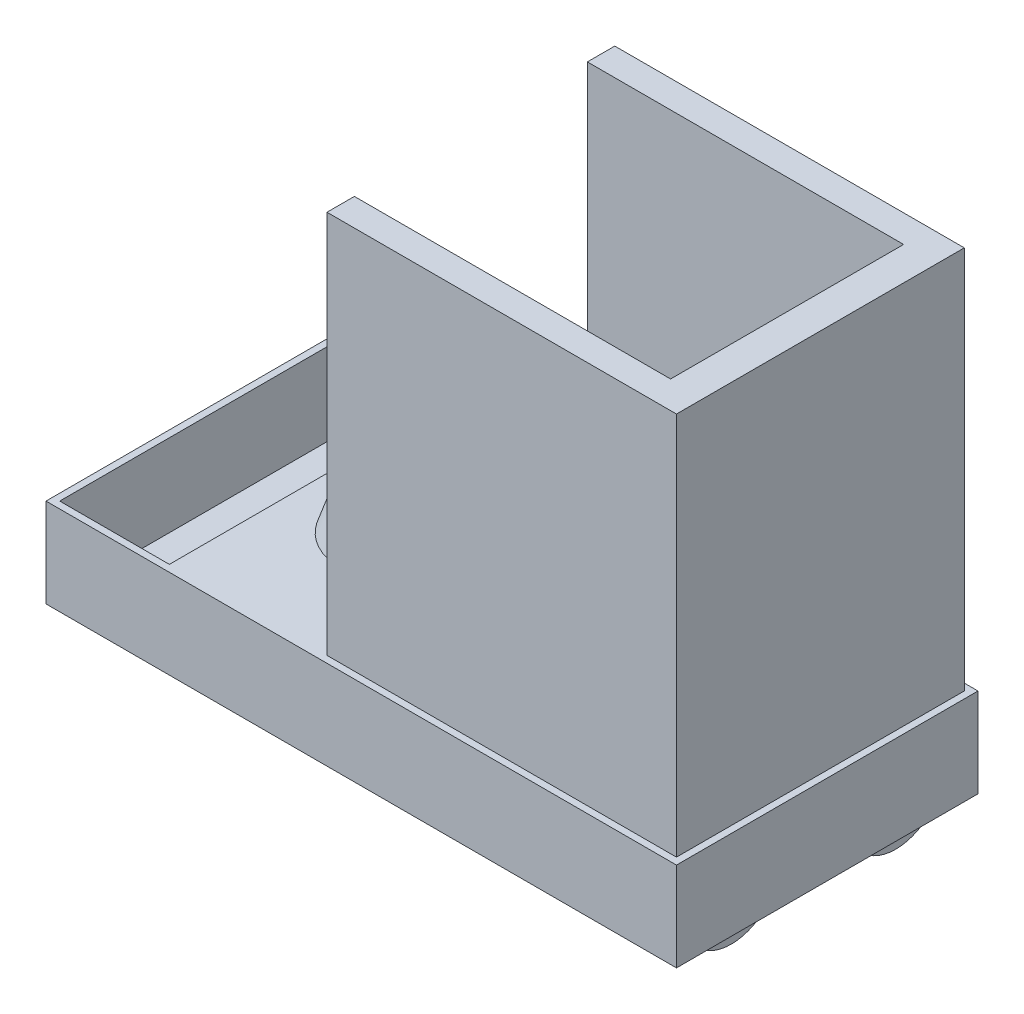
SolidWorks part; units mm, degrees
ref_plane "Front Plane" through (0, 0, 0) normal (0, 0, 1) x (1, 0, 0)
ref_plane "Top Plane" through (0, 0, 0) normal (0, 1, 0) x (1, 0, 0)
ref_plane "Right Plane" through (0, 0, 0) normal (1, 0, 0) x (0, 0, -1)
sketch "Chasis" plane through (0, 0, 0) normal (0, 1, 0) x (1, 0, 0)
  line L1 (-228.6, -139.7) -> (228.6, -139.7)
  line L2 (-228.6, -139.7) -> (-228.6, 139.7)
  line L3 (-228.6, 139.7) -> (228.6, 139.7)
  line L4 (228.6, -139.7) -> (228.6, 139.7)
  line L5 (-228.6, -139.7) -> (228.6, 139.7) construction
  line L6 (-228.6, 139.7) -> (228.6, -139.7) construction
  point P0 (0, 0)
  dimension "D1" = 457.2
  dimension "D2" = 279.4
extrude "Boss-Extrude1" add sketch "Chasis" along normal blind 82.55 contours L3 L4 L1 L2
ref_plane "Plane1" through (0, 25.4, 0) normal (0, -1, 0) x (-1, 0, 0)
sketch "Sketch3" plane through (0, 25.4, 0) normal (0, -1, 0) x (-1, 0, 0)
  line L0 (215.9, -76.2) -> (171.45, -76.2)
  line L1 (215.9, -76.2) -> (215.9, -120.65)
  line L2 (215.9, -120.65) -> (171.45, -120.65)
  line L3 (171.45, -76.2) -> (171.45, -120.65)
  line L4 (228.6, -139.7) -> (228.6, 139.7) construction
  line L5 (228.6, -139.7) -> (-228.6, -139.7) construction
  dimension "D1" = 44.45
  dimension "D2" = 44.45
  dimension "D3" = 12.7
  dimension "D4" = 19.05
revolve "Revolve1" add sketch "Sketch3" angle 360 about L0
mirror "Mirror1" about plane through (0, 0, 0) normal (0, 0, 1) of "Revolve1"
mirror "Mirror2" about plane through (0, 0, 0) normal (1, 0, 0) of "Revolve1", "Mirror1"
sketch "Sketch4" plane through (0, 82.55, 0) normal (0, 1, 0) x (1, 0, 0)
  line L0 (-228.6, -139.7) -> (228.6, -139.7) construction
  line L1 (222.25, 133.35) -> (-101.6, 133.35)
  line L2 (222.25, 133.35) -> (222.25, -133.35)
  line L3 (222.25, -133.35) -> (-101.6, -133.35)
  line L4 (-101.6, 133.35) -> (-101.6, 107.95)
  line L5 (222.25, 133.35) -> (-101.6, -133.35) construction
  line L6 (222.25, -133.35) -> (-101.6, 133.35) construction
  line L7 (228.6, -139.7) -> (228.6, 139.7) construction
  line L9 (-228.6, 139.7) -> (228.6, 139.7) construction
  line L10 (-101.6, 107.95) -> (191.4071, 107.95)
  line L11 (191.4071, 107.95) -> (191.4071, -107.95)
  line L12 (191.4071, -107.95) -> (-101.6, -107.95)
  line L13 (-101.6, -107.95) -> (-101.6, -133.35)
  point P0 (60.325, 0)
  point P5 (-128.4089, 107.95)
  point P13 (-156.7602, -108.6346)
  point P14 (244.9811, -107.95)
  dimension "D1" = 6.35
  dimension "D2" = 6.35
  dimension "D3" = 127
  dimension "D4" = 6.35
  dimension "D6" = 215.9
extrude "Boss-Extrude2" add sketch "Sketch4" along normal blind 355.6 contours L2 L3 L13 L12 L11 L10 L4 L1
sketch "Sketch5" plane through (0, 82.55, 0) normal (0, 1, 0) x (1, 0, 0)
  line L0 (-228.6, -139.7) -> (-228.6, 139.7) construction
  line L1 (-228.6, 139.7) -> (228.6, 139.7) construction
  circle A0 centre (-165.1, 0) radius 57.15
  point P4 (-165.1, 0)
  dimension "D1" = 114.3
  dimension "D3" = 139.7
  dimension "D2" = 63.5
ref_plane "Plane2" through (0, 120.65, 0) normal (0, 1, 0) x (1, 0, 0)
sketch "Sketch6" plane through (0, 120.65, 0) normal (0, 1, 0) x (1, 0, 0)
  line L0 (-228.6, -139.7) -> (228.6, -139.7) construction
  line L1 (-228.6, -139.7) -> (-228.6, 139.7) construction
  circle A0 centre (-165.1, 0) radius 44.45
  point P4 (0, 0)
  point P6 (-203.2906, -46.8976)
  dimension "D3" = 88.9
  dimension "D1" = 139.7
  dimension "D2" = 63.5
loft "Loft1" add profiles "Sketch6", "Sketch5"
sketch "Sketch10" plane through (-228.6, 0, 0) normal (-1, 0, 0) x (0, 0, 1)
  line L1 (-139.7, 82.55) -> (139.7, 82.55)
  line L2 (-139.7, 82.55) -> (-139.7, 0)
  line L3 (-139.7, 0) -> (139.7, 0)
  line L4 (139.7, 82.55) -> (139.7, 0)
extrude "Boss-Extrude3" add sketch "Sketch10" along normal blind 127 contours L1 L4 L3 L2
sketch "Sketch11" plane through (0, 82.55, 0) normal (0, 1, 0) x (1, 0, 0)
  line L0 (-355.6, -139.7) -> (228.6, -139.7) construction
  line L1 (-349.25, -133.35) -> (-247.65, -133.35)
  line L2 (-349.25, -133.35) -> (-349.25, 133.35)
  line L3 (-349.25, 133.35) -> (-247.65, 133.35)
  line L4 (-247.65, -133.35) -> (-247.65, 133.35)
  line L5 (-355.6, 139.7) -> (228.6, 139.7) construction
  line L6 (-355.6, 139.7) -> (-355.6, -139.7) construction
  dimension "D1" = 6.35
  dimension "D2" = 6.35
  dimension "D3" = 6.35
  dimension "D4" = 107.95
extrude "Cut-Extrude1" cut sketch "Sketch11" against normal blind 76.2 contours L3 L4 L1 L2
sketch "Sketch13" plane through (0, 120.65, 0) normal (0, 1, 0) x (1, 0, 0)
  line L1 (-139.7, 12.7) -> (-190.5, 12.7)
  line L2 (-139.7, 12.7) -> (-139.7, -12.7)
  line L3 (-139.7, -12.7) -> (-190.5, -12.7)
  line L4 (-190.5, 12.7) -> (-190.5, -12.7)
  line L5 (-139.7, 12.7) -> (-190.5, -12.7) construction
  line L6 (-139.7, -12.7) -> (-190.5, 12.7) construction
  point P0 (-165.1, 0)
  dimension "D1" = 50.8
  dimension "D2" = 25.4
extrude "Boss-Extrude5" add sketch "Sketch13" along normal blind 76.2
sketch "Sketch15" plane through (0, 0, 12.7) normal (0, 0, 1) x (1, 0, 0)
  line L0 (-190.5, 196.85) -> (-139.7, 196.85) construction
  circle A0 centre (-164.3321, 177.8) radius 12.7
  dimension "D1" = 25.4
  dimension "D2" = 19.05
extrude "Cut-Extrude2" cut sketch "Sketch15" against normal blind 25.4 contours A0
